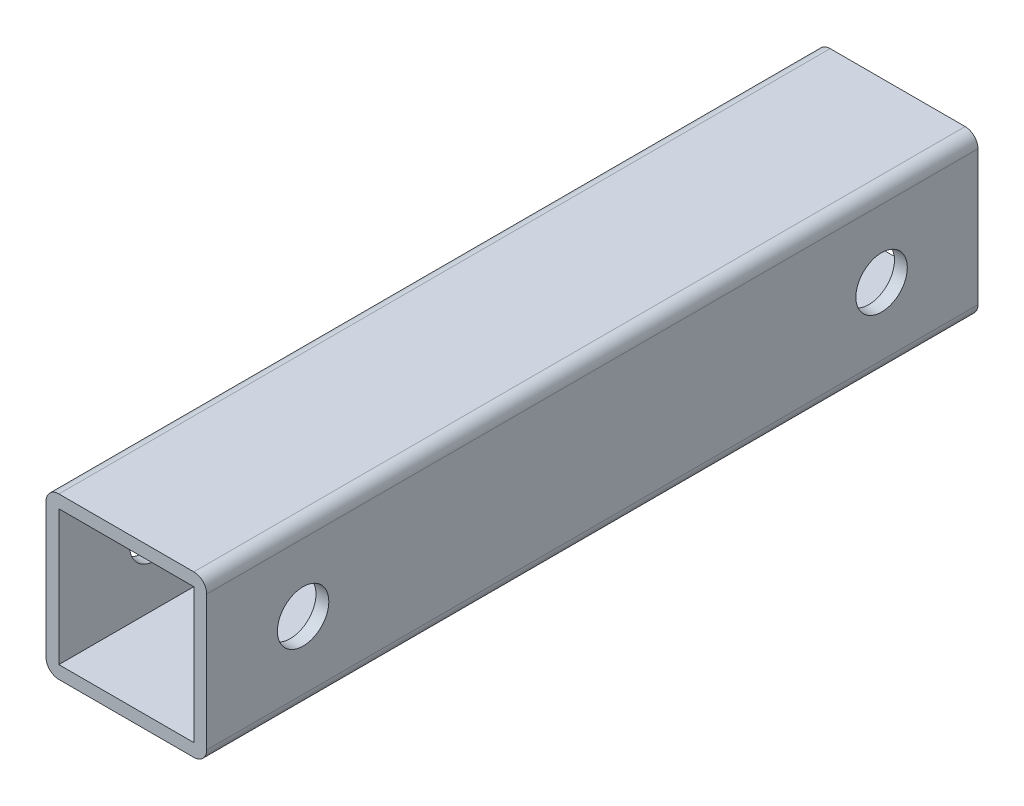
SolidWorks part; units mm, degrees
ref_plane "Front" through (0, 0, 0) normal (0, 0, 1) x (1, 0, 0)
ref_plane "Top" through (0, 0, 0) normal (0, 1, 0) x (1, 0, 0)
ref_plane "Right" through (0, 0, 0) normal (1, 0, 0) x (0, 0, -1)
sketch "Sketch1" plane through (0, 0, 0) normal (0, 0, 1) x (1, 0, 0)
  line L1 (-12.5, -12.5) -> (12.5, -12.5)
  line L2 (-12.5, -12.5) -> (-12.5, 12.5)
  line L3 (-12.5, 12.5) -> (12.5, 12.5)
  line L4 (12.5, -12.5) -> (12.5, 12.5)
  line L5 (-12.5, -12.5) -> (12.5, 12.5) construction
  line L6 (-12.5, 12.5) -> (12.5, -12.5) construction
  point P0 (0, 0)
  dimension "D1" = 25
  dimension "D2" = 25
extrude "Extrude-Thin1" add sketch "Sketch1" along normal blind 60 and the other way blind 60 thin thin type one direction reverse wall 2
fillet "Fillet1" radius 2 4 edges at (-12.5, -12.5, 0) (12.5, -12.5, 0) (-12.5, 12.5, 0) (12.5, 12.5, 0)
sketch "Sketch2" plane through (12.5, 0, 0) normal (1, 0, 0) x (0, 0, -1)
  line L0 (60, 12.5) -> (-60, 12.5) construction
  line L1 (-204, 12.5) -> (76, 12.5) construction
  line L2 (60, 10.5) -> (60, -10.5) construction
  line L3 (-60, 10.5) -> (-60, -10.5) construction
  circle A0 centre (-45, 0) radius 4
  circle A1 centre (45, 0) radius 4
  dimension "D1" = 8
  dimension "D2" = 8
  dimension "D3" = 15
  dimension "D4" = 15
  dimension "D5" = 12.5
  dimension "D6" = 12.5
extrude "Cut-Extrude1" cut sketch "Sketch2" against normal through all
